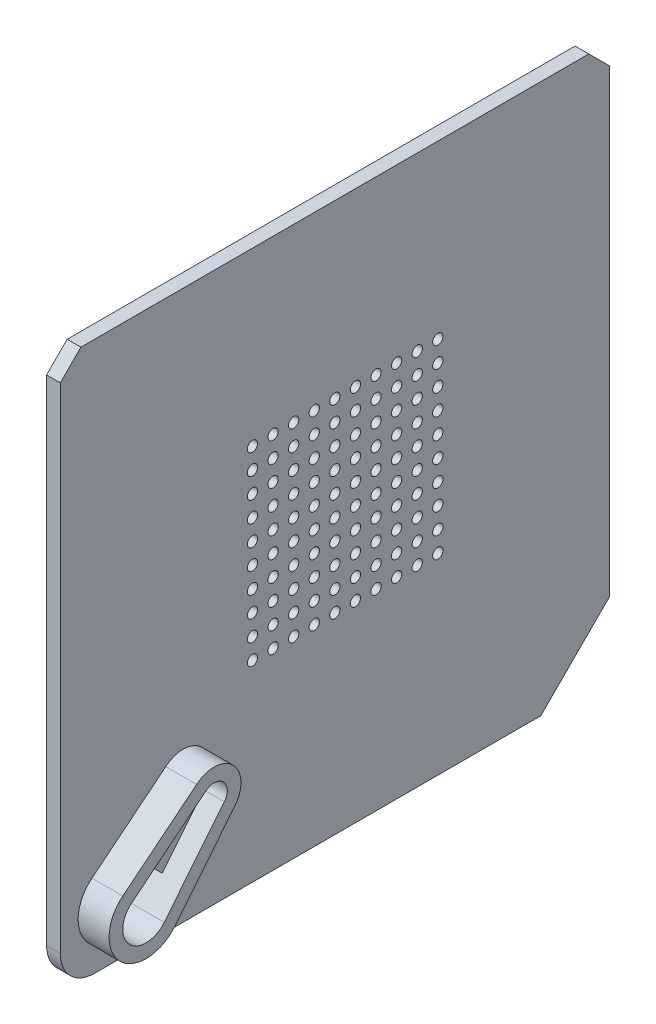
SolidWorks part; units mm, degrees
ref_plane "前视基准面" through (0, 0, 0) normal (0, 0, 1) x (1, 0, 0)
ref_plane "上视基准面" through (0, 0, 0) normal (0, 1, 0) x (1, 0, 0)
ref_plane "右视基准面" through (0, 0, 0) normal (1, 0, 0) x (0, 0, -1)
other "Configuration Table"
sketch "草图1" plane through (0, 0, 0) normal (1, 0, 0) x (0, 0, -1)
  line L0 (70, 0) -> (80, 10)
  line L1 (5, 0) -> (70, 0)
  line L2 (0, 5) -> (0, 77)
  line L3 (3, 80) -> (77, 80)
  line L4 (80, 10) -> (80, 77)
  line L5 (0, 77) -> (3, 80)
  line L6 (77, 80) -> (80, 77)
  line L8 (5.8624, 10.644) -> (16.6417, 19.3589)
  line L9 (10.6438, 5.8622) -> (19.3976, 16.6881)
  arc A0 (5.8624, 10.644) -> (10.6438, 5.8622) centre (8, 8) ccw
  arc A1 (5, 0) -> (0, 5) centre (5, 5) cw
  arc A2 (19.3976, 16.6881) -> (16.6417, 19.3589) centre (17.8995, 17.8995) ccw
  circle A3 centre (28, 55) radius 0.75
  circle A4 centre (28, 52) radius 0.75
  circle A5 centre (28, 49) radius 0.75
  circle A6 centre (28, 46) radius 0.75
  circle A7 centre (28, 43) radius 0.75
  circle A8 centre (28, 40) radius 0.75
  circle A9 centre (28, 37) radius 0.75
  circle A10 centre (28, 34) radius 0.75
  circle A11 centre (28, 31) radius 0.75
  circle A12 centre (28, 28) radius 0.75
  circle A13 centre (31, 52) radius 0.75
  circle A14 centre (31, 49) radius 0.75
  circle A15 centre (31, 46) radius 0.75
  circle A16 centre (31, 43) radius 0.75
  circle A17 centre (31, 40) radius 0.75
  circle A18 centre (31, 37) radius 0.75
  circle A19 centre (31, 34) radius 0.75
  circle A20 centre (31, 31) radius 0.75
  circle A21 centre (31, 28) radius 0.75
  circle A22 centre (34, 52) radius 0.75
  circle A23 centre (34, 49) radius 0.75
  circle A24 centre (34, 46) radius 0.75
  circle A25 centre (34, 43) radius 0.75
  circle A26 centre (34, 40) radius 0.75
  circle A27 centre (34, 37) radius 0.75
  circle A28 centre (34, 34) radius 0.75
  circle A29 centre (34, 31) radius 0.75
  circle A30 centre (34, 28) radius 0.75
  circle A31 centre (37, 52) radius 0.75
  circle A32 centre (37, 49) radius 0.75
  circle A33 centre (37, 46) radius 0.75
  circle A34 centre (37, 43) radius 0.75
  circle A35 centre (37, 40) radius 0.75
  circle A36 centre (37, 37) radius 0.75
  circle A37 centre (37, 34) radius 0.75
  circle A38 centre (37, 31) radius 0.75
  circle A39 centre (37, 28) radius 0.75
  circle A40 centre (40, 52) radius 0.75
  circle A41 centre (40, 49) radius 0.75
  circle A42 centre (40, 46) radius 0.75
  circle A43 centre (40, 43) radius 0.75
  circle A44 centre (40, 40) radius 0.75
  circle A45 centre (40, 37) radius 0.75
  circle A46 centre (40, 34) radius 0.75
  circle A47 centre (40, 31) radius 0.75
  circle A48 centre (40, 28) radius 0.75
  circle A49 centre (43, 52) radius 0.75
  circle A50 centre (43, 49) radius 0.75
  circle A51 centre (43, 46) radius 0.75
  circle A52 centre (43, 43) radius 0.75
  circle A53 centre (43, 40) radius 0.75
  circle A54 centre (43, 37) radius 0.75
  circle A55 centre (43, 34) radius 0.75
  circle A56 centre (43, 31) radius 0.75
  circle A57 centre (43, 28) radius 0.75
  circle A58 centre (46, 52) radius 0.75
  circle A59 centre (46, 49) radius 0.75
  circle A60 centre (46, 46) radius 0.75
  circle A61 centre (46, 43) radius 0.75
  circle A62 centre (46, 40) radius 0.75
  circle A63 centre (46, 37) radius 0.75
  circle A64 centre (46, 34) radius 0.75
  circle A65 centre (46, 31) radius 0.75
  circle A66 centre (46, 28) radius 0.75
  circle A67 centre (49, 52) radius 0.75
  circle A68 centre (49, 49) radius 0.75
  circle A69 centre (49, 46) radius 0.75
  circle A70 centre (49, 43) radius 0.75
  circle A71 centre (49, 40) radius 0.75
  circle A72 centre (49, 37) radius 0.75
  circle A73 centre (49, 34) radius 0.75
  circle A74 centre (49, 31) radius 0.75
  circle A75 centre (49, 28) radius 0.75
  circle A76 centre (52, 52) radius 0.75
  circle A77 centre (52, 49) radius 0.75
  circle A78 centre (52, 46) radius 0.75
  circle A79 centre (52, 43) radius 0.75
  circle A80 centre (52, 40) radius 0.75
  circle A81 centre (52, 37) radius 0.75
  circle A82 centre (52, 34) radius 0.75
  circle A83 centre (52, 31) radius 0.75
  circle A84 centre (52, 28) radius 0.75
  circle A85 centre (55, 52) radius 0.75
  circle A86 centre (55, 49) radius 0.75
  circle A87 centre (55, 46) radius 0.75
  circle A88 centre (55, 43) radius 0.75
  circle A89 centre (55, 40) radius 0.75
  circle A90 centre (55, 37) radius 0.75
  circle A91 centre (55, 34) radius 0.75
  circle A92 centre (55, 31) radius 0.75
  circle A93 centre (55, 28) radius 0.75
  circle A94 centre (31, 55) radius 0.75
  circle A95 centre (34, 55) radius 0.75
  circle A96 centre (37, 55) radius 0.75
  circle A97 centre (40, 55) radius 0.75
  circle A98 centre (43, 55) radius 0.75
  circle A99 centre (46, 55) radius 0.75
  circle A100 centre (49, 55) radius 0.75
  circle A101 centre (52, 55) radius 0.75
  circle A102 centre (55, 55) radius 0.75
  point P1 (80, 80)
  point P2 (0, 80)
  point P3 (80, 0)
  point P9 (0, 0)
  dimension "D3" = 6.8
  dimension "D6" = 5
  dimension "D7" = 14
  dimension "D14" = 1.5
  dimension "D19" = 52
  dimension "D21" = 55
  dimension "D1" = 80
  dimension "D2" = 80
  dimension "D4" = 8
  dimension "D5" = 8
  dimension "D8" = 10.8259
  dimension "D12" = 17.8995
  dimension "D13" = 13.8616
  dimension "D15" = 28
  dimension "D16" = 25
  dimension "D20" = 3
  dimension "D17" = 10
  dimension "D18" = 10
extrude "凸台-拉伸1" add sketch "草图1" along normal blind 2
sketch "草图2" plane through (2, 0, 0) normal (1, 0, 0) x (0, 0, -1)
  line L0 (10.6438, 5.8622) -> (19.3976, 16.6881) construction
  line L1 (16.6417, 19.3589) -> (5.8624, 10.644) construction
  line L2 (10.6438, 5.8622) -> (19.3976, 16.6881)
  line L3 (16.6417, 19.3589) -> (5.8624, 10.644)
  line L4 (15.3641, 20.8979) -> (4.605, 12.1993)
  line L5 (12.199, 4.6047) -> (20.9528, 15.4306)
  arc A0 (5.8624, 10.644) -> (10.6438, 5.8622) centre (8, 8) ccw construction
  arc A1 (19.3976, 16.6881) -> (16.6417, 19.3589) centre (17.8995, 17.8995) ccw construction
  arc A2 (5.8624, 10.644) -> (10.6438, 5.8622) centre (8, 8) ccw
  arc A3 (19.3976, 16.6881) -> (16.6417, 19.3589) centre (17.8995, 17.8995) ccw
  arc A4 (4.605, 12.1993) -> (12.199, 4.6047) centre (8, 8) ccw
  arc A5 (20.9528, 15.4306) -> (15.3641, 20.8979) centre (17.8995, 17.8995) ccw
  dimension "D1" = 2
extrude "凸台-拉伸2" add sketch "草图2" along normal blind 1.5
sketch "草图3" plane through (0, 0, 0) normal (-1, 0, 0) x (0, 0, 1)
  line L0 (-16.6417, 19.3589) -> (-5.8624, 10.644) construction
  line L1 (-10.6438, 5.8622) -> (-19.3976, 16.6881) construction
  line L2 (-16.6417, 19.3589) -> (-9.2063, 13.3475)
  line L3 (-13.3477, 9.2061) -> (-19.3976, 16.6881)
  line L4 (-9.2063, 13.3475) -> (-13.3477, 9.2061)
  arc A0 (-16.6417, 19.3589) -> (-19.3976, 16.6881) centre (-17.8995, 17.8995) ccw construction
  arc A1 (-16.6417, 19.3589) -> (-19.3976, 16.6881) centre (-17.8995, 17.8995) ccw
extrude "凸台-拉伸3" add sketch "草图3" against normal blind 1.5
sketch "草图4" plane through (1.5, 0, 0) normal (1, 0, 0) x (0, 0, -1)
  line L0 (12.2123, 11.9856) -> (13.9801, 13.7533) construction
  line L1 (11.7881, 12.4098) -> (13.5558, 14.1776)
  line L2 (12.6366, 11.5613) -> (14.4044, 13.3291)
  line L3 (15.4427, 15.2159) -> (17.2105, 16.9837) construction
  line L4 (15.0184, 15.6402) -> (16.7862, 17.408)
  line L5 (15.867, 14.7917) -> (17.6347, 16.5594)
  line L6 (13.3477, 9.2061) -> (9.2063, 13.3475) construction
  arc A0 (11.7881, 12.4098) -> (12.6366, 11.5613) centre (12.2123, 11.9856) ccw
  arc A1 (14.4044, 13.3291) -> (13.5558, 14.1776) centre (13.9801, 13.7533) ccw
  arc A2 (15.0184, 15.6402) -> (15.867, 14.7917) centre (15.4427, 15.2159) ccw
  arc A3 (17.6347, 16.5594) -> (16.7862, 17.408) centre (17.2105, 16.9837) ccw
  point P2 (13.0962, 12.8695)
  point P7 (16.3266, 16.0998)
  dimension "D1" = 1.2
  dimension "D2" = 2.5
  dimension "D3" = 90
  dimension "D4" = 1.2
  dimension "D5" = 2.5
extrude "切除-拉伸1" cut sketch "草图4" against normal blind 1.5
sketch "草图5" plane through (3.5, 0, 0) normal (1, 0, 0) x (0, 0, -1)
  line L0 (10.6438, 5.8622) -> (19.3976, 16.6881) construction
  line L1 (19.3976, 16.6881) -> (13.3477, 9.2061) construction
  line L2 (15.3641, 20.8979) -> (4.605, 12.1993)
  line L3 (12.199, 4.6047) -> (20.9528, 15.4306)
  line L4 (15.3641, 20.8979) -> (4.605, 12.1993)
  line L5 (12.199, 4.6047) -> (20.9528, 15.4306)
  line L6 (16.6417, 19.3589) -> (5.8624, 10.644) construction
  line L7 (10.6438, 5.8622) -> (19.3976, 16.6881)
  line L8 (19.3976, 16.6881) -> (13.3477, 9.2061)
  line L9 (16.6417, 19.3589) -> (5.8624, 10.644)
  arc A0 (19.3976, 16.6881) -> (16.6417, 19.3589) centre (17.8995, 17.8995) ccw construction
  arc A1 (5.8624, 10.644) -> (10.6438, 5.8622) centre (8, 8) ccw construction
  arc A2 (20.9528, 15.4306) -> (15.3641, 20.8979) centre (17.8995, 17.8995) ccw
  arc A3 (4.605, 12.1993) -> (12.199, 4.6047) centre (8, 8) ccw
  arc A4 (20.9528, 15.4306) -> (15.3641, 20.8979) centre (17.8995, 17.8995) ccw
  arc A5 (4.605, 12.1993) -> (12.199, 4.6047) centre (8, 8) ccw
  arc A6 (19.3976, 16.6881) -> (16.6417, 19.3589) centre (17.8995, 17.8995) ccw
  arc A7 (5.8624, 10.644) -> (10.6438, 5.8622) centre (8, 8) ccw
  arc M5 (20.9528, 15.4306) -> (15.3641, 20.8979) centre (17.8995, 17.8995) ccw
  line M6 (15.3641, 20.8979) -> (4.605, 12.1993)
  arc M7 (4.605, 12.1993) -> (12.199, 4.6047) centre (8, 8) ccw
  line M8 (12.199, 4.6047) -> (20.9528, 15.4306)
  line M9 (19.3976, 16.6881) -> (10.6438, 5.8622)
  arc M10 (10.6438, 5.8622) -> (5.8624, 10.644) centre (8, 8) cw
  line M11 (5.8624, 10.644) -> (16.6417, 19.3589)
  arc M12 (16.6417, 19.3589) -> (19.3976, 16.6881) centre (17.8995, 17.8995) cw
  dimension "D1" = 0
extrude "凸台-拉伸4" add sketch "草图5" along normal blind 3 contours L7 M8 M5 M6 M7 M12 M9 M10 M11
sketch "草图6" plane through (1.5, 0, 0) normal (1, 0, 0) x (0, 0, -1)
  line L0 (12.6366, 11.5613) -> (14.4044, 13.3291) construction
  line L1 (13.5558, 14.1776) -> (11.7881, 12.4098) construction
  line L2 (15.867, 14.7917) -> (17.6347, 16.5594) construction
  line L3 (16.6417, 19.3589) -> (9.2063, 13.3475)
  line L4 (9.2063, 13.3475) -> (13.3477, 9.2061)
  line L5 (13.3477, 9.2061) -> (19.3976, 16.6881)
  line L6 (16.6417, 19.3589) -> (9.2063, 13.3475)
  line L7 (9.2063, 13.3475) -> (13.3477, 9.2061)
  line L8 (13.3477, 9.2061) -> (19.3976, 16.6881)
  line L9 (16.7862, 17.408) -> (15.0184, 15.6402) construction
  line L10 (12.6366, 11.5613) -> (14.4044, 13.3291)
  line L11 (13.5558, 14.1776) -> (11.7881, 12.4098)
  line L12 (15.867, 14.7917) -> (17.6347, 16.5594)
  line L13 (16.7862, 17.408) -> (15.0184, 15.6402)
  arc A0 (11.7881, 12.4098) -> (12.6366, 11.5613) centre (12.2123, 11.9856) ccw construction
  arc A1 (19.3976, 16.6881) -> (16.6417, 19.3589) centre (17.8995, 17.8995) ccw
  arc A2 (19.3976, 16.6881) -> (16.6417, 19.3589) centre (17.8995, 17.8995) ccw
  arc A3 (14.4044, 13.3291) -> (13.5558, 14.1776) centre (13.9801, 13.7533) ccw construction
  arc A4 (17.6347, 16.5594) -> (16.7862, 17.408) centre (17.2105, 16.9837) ccw construction
  arc A5 (15.0184, 15.6402) -> (15.867, 14.7917) centre (15.4427, 15.2159) ccw construction
  arc A6 (11.7881, 12.4098) -> (12.6366, 11.5613) centre (12.2123, 11.9856) ccw
  arc A7 (14.4044, 13.3291) -> (13.5558, 14.1776) centre (13.9801, 13.7533) ccw
  arc A8 (17.6347, 16.5594) -> (16.7862, 17.408) centre (17.2105, 16.9837) ccw
  arc A9 (15.0184, 15.6402) -> (15.867, 14.7917) centre (15.4427, 15.2159) ccw
  dimension "D1" = 0
extrude "凸台-拉伸5" add sketch "草图6" along normal blind 2
